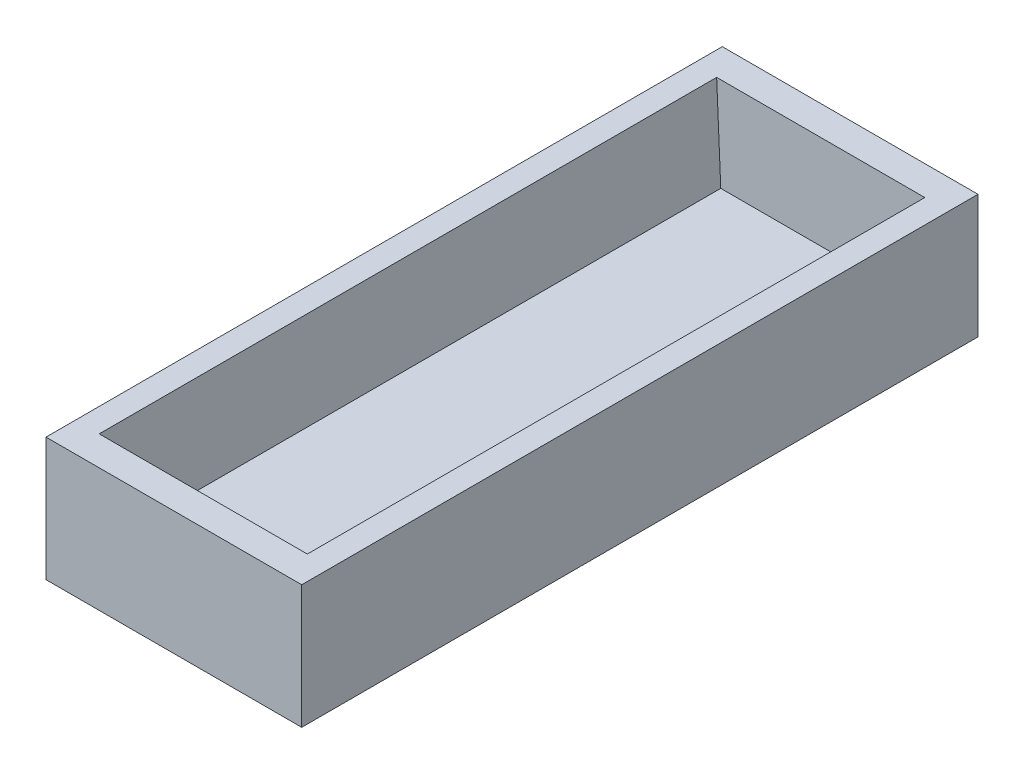
SolidWorks part; units mm, degrees
ref_plane "Front Plane" through (0, 0, 0) normal (0, 0, 1) x (1, 0, 0)
ref_plane "Top Plane" through (0, 0, 0) normal (0, 1, 0) x (1, 0, 0)
ref_plane "Right Plane" through (0, 0, 0) normal (1, 0, 0) x (0, 0, -1)
sketch "Sketch1" plane through (0, 0, 0) normal (0, 0, 1) x (1, 0, 0)
  line L0 (0, 0) -> (0, 107.95)
  line L1 (0, 0) -> (224.0826, 0) construction
  line L2 (0, 0) -> (0, 107.95) construction
  line L3 (0, 107.95) -> (224.0826, 107.95) construction
  line L4 (7.611, 6.35) -> (7.611, 107.95) construction
  line L5 (0, 107.95) -> (3.175, 107.95)
  line L6 (3.175, 107.95) -> (7.611, 6.35)
  line L7 (7.611, 6.35) -> (50.791, 6.35)
  line L8 (50.791, 6.35) -> (55.2269, 107.95)
  line L9 (55.2269, 107.95) -> (55.2269, 0) construction
  line L10 (55.2269, 107.95) -> (58.4019, 107.95)
  line L11 (58.4019, 107.95) -> (58.4019, 0) construction
  line L12 (7.611, 107.95) -> (3.175, 107.95) construction
  line L13 (58.4019, 107.95) -> (62.8379, 6.35)
  line L14 (62.8379, 6.35) -> (106.0179, 6.35)
  line L15 (106.0179, 6.35) -> (110.4538, 107.95)
  line L16 (110.4538, 107.95) -> (113.6288, 107.95)
  line L17 (113.6288, 107.95) -> (118.0648, 6.35)
  line L18 (118.0648, 6.35) -> (161.2448, 6.35)
  line L19 (161.2448, 6.35) -> (165.6807, 107.95)
  line L20 (165.6807, 107.95) -> (168.8557, 107.95)
  line L21 (168.8557, 107.95) -> (173.2917, 6.35)
  line L22 (173.2917, 6.35) -> (216.4717, 6.35)
  line L23 (216.4717, 6.35) -> (220.9076, 107.95)
  line L24 (220.9076, 107.95) -> (224.0826, 107.95)
  line L25 (224.0826, 107.95) -> (224.0826, 0)
  line L26 (224.0826, 0) -> (0, 0)
  line L27 (110.4538, 107.95) -> (110.4538, 0) construction
  line L28 (113.6288, 107.95) -> (113.6288, 0) construction
  line L29 (165.6807, 107.95) -> (165.6807, 0) construction
  line L30 (168.8557, 107.95) -> (168.8557, 0) construction
  line L31 (50.791, 6.35) -> (62.8379, 6.35) construction
  line L32 (106.0179, 6.35) -> (118.0648, 6.35) construction
  line L33 (161.2448, 6.35) -> (173.2917, 6.35) construction
  line L34 (112.0413, 113.03) -> (112.0413, -30.1165) construction
  line L35 (-40.3587, 141.2445) -> (-40.3587, -34.167) construction
  line L36 (264.4413, 143.4606) -> (264.4413, -34.167) construction
  line L37 (50.791, 6.35) -> (50.791, 113.03) construction
  line L38 (92.9913, 151.13) -> (131.0913, 151.13) construction
  line L39 (92.9913, 151.13) -> (92.9913, 113.03) construction
  line L40 (92.9913, 113.03) -> (131.0913, 113.03) construction
  line L41 (131.0913, 151.13) -> (131.0913, 113.03) construction
  line L42 (12.691, 113.03) -> (50.791, 113.03) construction
  line L43 (12.691, 113.03) -> (12.691, 151.13) construction
  line L44 (12.691, 151.13) -> (50.791, 151.13) construction
  line L45 (50.791, 113.03) -> (50.791, 151.13) construction
  line L46 (71.8911, 162.5443) -> (71.8911, 143.1127) construction
  point P38 (112.0413, 113.03)
  point P43 (50.791, 113.03)
  point P45 (31.741, 151.13)
  point P46 (112.0413, 151.13)
  dimension "D1" = 52.0519
  dimension "D2" = 107.95
  dimension "D3" = 43.18
  dimension "D4" = 6.35
  dimension "D5" = 2.5
  dimension "D6" = 2.5
  dimension "D7" = 3.175
  dimension "D8" = 3.175
  dimension "D9" = 4.436
  dimension "D10" = 3.175
  dimension "D11" = 3.175
  dimension "D12" = 3.175
  dimension "D13" = 2.5
  dimension "D14" = 2.5
  dimension "D15" = 2.5
  dimension "D16" = 2.5
  dimension "D17" = 2.5
  dimension "D18" = 2.5
  dimension "D19" = 43.18
  dimension "D20" = 43.18
  dimension "D21" = 43.18
  dimension "D22" = 224.0826
  dimension "D23" = 112.0413
  dimension "D24" = 304.8
  dimension "D25" = 40.3587
  dimension "D26" = 40.3587
  dimension "D27" = 38.1
  dimension "D28" = 38.1
  dimension "D29" = 38.1
  dimension "D30" = 38.1
  dimension "D31" = 5.08
  dimension "D32" = 80.3004
  dimension "D33" = 40.1502
extrude "Boss-Extrude1" add sketch "Sketch1" along normal blind 146.05
sketch "Sketch2" plane through (0, 0, 146.05) normal (0, 0, 1) x (1, 0, 0)
  line L0 (3.175, 107.95) -> (55.2269, 107.95)
  line L1 (55.2269, 107.95) -> (50.791, 6.35)
  line L2 (50.791, 6.35) -> (7.611, 6.35)
  line L3 (7.611, 6.35) -> (3.175, 107.95)
  line L4 (58.4019, 107.95) -> (62.8379, 6.35)
  line L5 (62.8379, 6.35) -> (106.0179, 6.35)
  line L6 (106.0179, 6.35) -> (110.4538, 107.95)
  line L7 (110.4538, 107.95) -> (58.4019, 107.95)
  line L8 (113.6288, 107.95) -> (118.0648, 6.35)
  line L9 (118.0648, 6.35) -> (161.2448, 6.35)
  line L10 (161.2448, 6.35) -> (165.6807, 107.95)
  line L11 (165.6807, 107.95) -> (113.6288, 107.95)
  line L12 (168.8557, 107.95) -> (173.2917, 6.35)
  line L13 (173.2917, 6.35) -> (216.4717, 6.35)
  line L14 (216.4717, 6.35) -> (220.9076, 107.95)
  line L15 (220.9076, 107.95) -> (168.8557, 107.95)
extrude "Boss-Extrude2" add sketch "Sketch2" against normal blind 6.35
ref_plane "Plane1" through (0, 0, 73.025) normal (0, 0, -1) x (-1, 0, 0)
mirror "Mirror1" about plane through (0, 0, 73.025) normal (0, 0, -1) of "Boss-Extrude2"
ref_plane "Plane2" through (112.0413, 0, 0) normal (1, 0, 0) x (0, 0, -1)
sketch "Sketch3" plane through (0, 107.95, 0) normal (0, 1, 0) x (1, 0, 0)
  line L1 (-24.2108, -174.0169) -> (250.1805, -174.0169)
  line L2 (-24.2108, -174.0169) -> (-24.2108, 38.1413)
  line L3 (-24.2108, 38.1413) -> (250.1805, 38.1413)
  line L4 (250.1805, -174.0169) -> (250.1805, 38.1413)
extrude "Cut-Extrude1" cut sketch "Sketch3" against normal offset from surface (81.28 mm away) 20.32 up to face at (84.4279, 6.35, 73.025)
sketch "Sketch4" plane through (0, 26.67, 0) normal (0, 1, 0) x (1, 0, 0)
  line L0 (56.8144, 0) -> (56.8144, -146.05) construction
  line L1 (224.0826, 0) -> (0, 0) construction
  line L2 (224.0826, -146.05) -> (0, -146.05) construction
  line L3 (112.0413, 0) -> (112.0413, -146.05) construction
  line L4 (61.9507, -6.35) -> (61.9507, -139.7) construction
  line L6 (51.6781, -139.7) -> (51.6781, -6.35) construction
  line L7 (61.9507, -6.35) -> (61.9507, -139.7) construction
  line L8 (51.6781, -139.7) -> (51.6781, -6.35) construction
  line L9 (106.905, -139.7) -> (106.905, -6.35) construction
  line L11 (56.8144, 0) -> (0, 0)
  line L12 (56.8144, 0) -> (56.8144, -146.05)
  line L13 (56.8144, -146.05) -> (0, -146.05)
  line L14 (0, 0) -> (0, -146.05)
  line L15 (112.0413, 0) -> (224.0826, 0)
  line L16 (112.0413, 0) -> (112.0413, -146.05)
  line L17 (112.0413, -146.05) -> (224.0826, -146.05)
  line L18 (224.0826, 0) -> (224.0826, -146.05)
  dimension "D1" = 5.1363
  dimension "D2" = 10.2725
  dimension "D3" = 5.1363
extrude "Cut-Extrude2" cut sketch "Sketch4" against normal through all
equation "\"D8@Sketch1\"=\"D7@Sketch1\""
equation "\"D10@Sketch1\"=\"D8@Sketch1\""
equation "\"D11@Sketch1\"=\"D7@Sketch1\""
equation "\"D12@Sketch1\"=\"D7@Sketch1\""
equation "\"D13@Sketch1\"=\"D5@Sketch1\""
equation "\"D6@Sketch1\"=\"D5@Sketch1\""
equation "\"D14@Sketch1\"=\"D5@Sketch1\""
equation "\"D15@Sketch1\"=\"D5@Sketch1\""
equation "\"D16@Sketch1\"=\"D5@Sketch1\""
equation "\"D17@Sketch1\"=\"D5@Sketch1\""
equation "\"D18@Sketch1\"=\"D5@Sketch1\""
equation "\"D19@Sketch1\"=\"D3@Sketch1\""
equation "\"D20@Sketch1\"=\"D3@Sketch1\""
equation "\"D21@Sketch1\"=\"D3@Sketch1\""
equation "\"D23@Sketch1\"=\"D22@Sketch1\"/2"
equation "\"D25@Sketch1\"=(\"D24@Sketch1\"-\"D22@Sketch1\")/2"
equation "\"D33@Sketch1\"=\"D32@Sketch1\"/2"
equation "\"D1@Sketch4\"=\"D2@Sketch4\"/2"
equation "\"D3@Sketch4\"=\"D1@Sketch4\""
